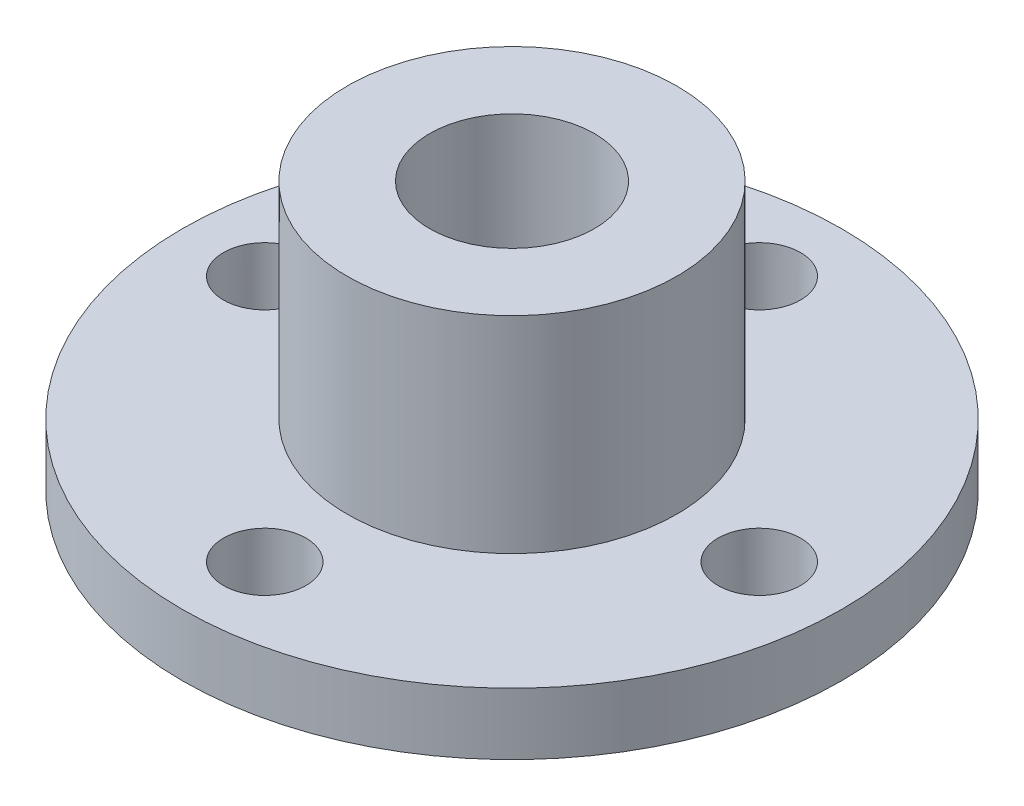
SolidWorks part; units mm, degrees
ref_plane "Front Plane" through (0, 0, 0) normal (0, 0, 1) x (1, 0, 0)
ref_plane "Top Plane" through (0, 0, 0) normal (0, 1, 0) x (1, 0, 0)
ref_plane "Right Plane" through (0, 0, 0) normal (1, 0, 0) x (0, 0, -1)
sketch "Sketch1" plane through (0, 0, 0) normal (0, 0, 1) x (1, 0, 0)
  line L0 (0, 0) -> (0, -13)
  line L1 (0, -13) -> (12, -13)
  line L2 (12, -13) -> (12, -10)
  line L3 (12, -10) -> (4, -10)
  line L4 (4, -10) -> (4, 0)
  line L5 (4, 0) -> (0, 0)
  line L6 (-4, -13) -> (-4, 3.8954) construction
  dimension "D1" = 8
  dimension "D2" = 4
  dimension "D3" = 13
  dimension "D4" = 10
  dimension "D5" = 4
revolve "Revolve1" add sketch "Sketch1" angle 360 about L6
sketch "Sketch2" plane through (0, -10, 0) normal (0, 1, 0) x (1, 0, 0)
  line L0 (-4, 16) -> (-4, 8) construction
  circle A0 centre (-4, 0) radius 16 construction
  circle A1 centre (-4, 0) radius 8 construction
  circle A2 centre (-4, 12) radius 2
  dimension "D1" = 4
extrude "Cut-Extrude1" cut sketch "Sketch2" against normal up to surface (3 mm away) up to face at (-4, -13, -16)
pattern_circular "CirPattern1" count 4 over 360 about axis through (-4, 0, 0) along (0, 1, 0) of "Cut-Extrude1"
